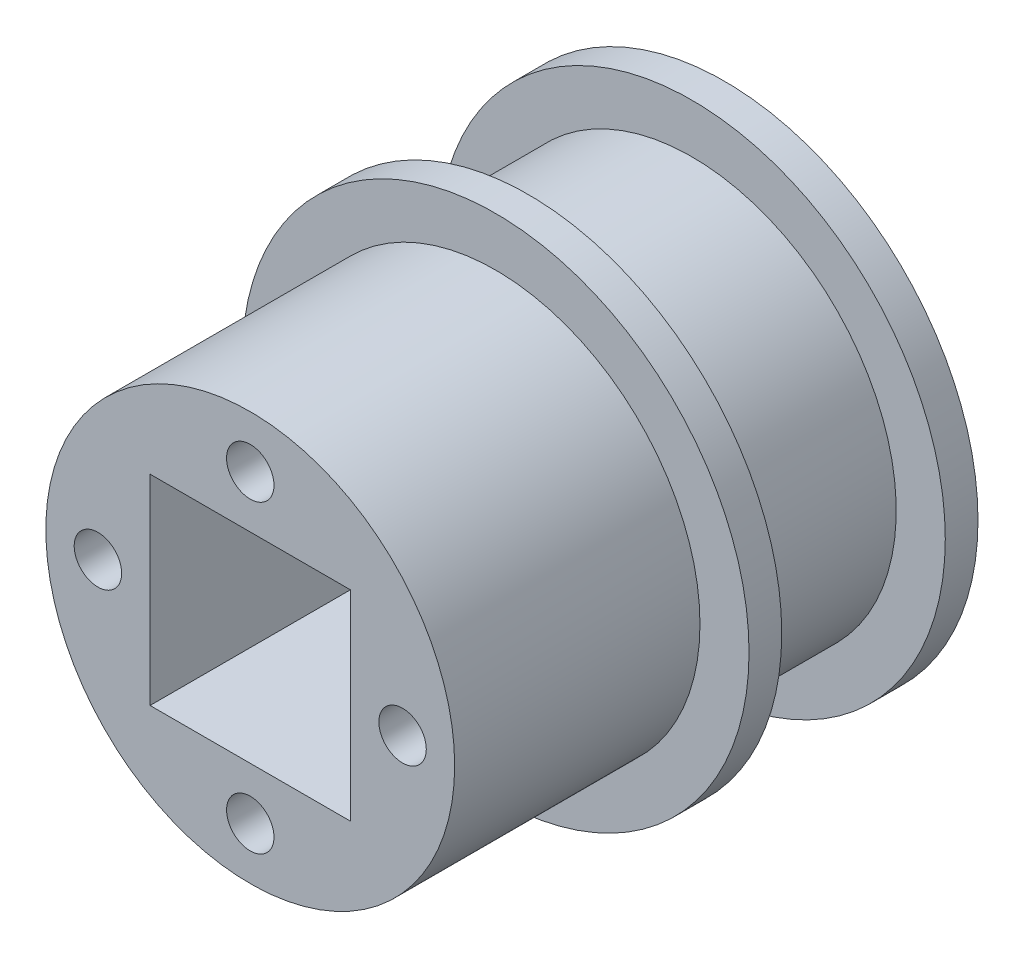
SolidWorks part; units mm, degrees
ref_plane "Front Plane" through (0, 0, 0) normal (0, 0, 1) x (1, 0, 0)
ref_plane "Top Plane" through (0, 0, 0) normal (0, 1, 0) x (1, 0, 0)
ref_plane "Right Plane" through (0, 0, 0) normal (1, 0, 0) x (0, 0, -1)
sketch "Sketch1" plane through (0, 0, 0) normal (0, 0, 1) x (1, 0, 0)
  circle A0 centre (0, 0) radius 12.5
  dimension "D2" = 25
extrude "Boss-Extrude1" add sketch "Sketch1" along normal mid plane 15
sketch "Sketch10" plane through (0, 0, 7.5) normal (0, 0, 1) x (1, 0, 0)
  circle A0 centre (0, 0) radius 12.5
  dimension "D1" = 25
sketch "Sketch13" plane through (0, 0, -7.5) normal (0, 0, -1) x (-1, 0, 0)
  circle A0 centre (0, 0) radius 15.5
  circle A1 centre (0, 0) radius 12.5 construction
  point P2 (0, 0)
  point P3 (0, 0)
  dimension "D1" = 3
extrude "Boss-Extrude2" add sketch "Sketch13" along normal blind 2
sketch "Sketch14" plane through (0, 0, -9.5) normal (0, 0, -1) x (-1, 0, 0)
  circle A0 centre (0, 0) radius 12.5
  circle A1 centre (0, 0) radius 12.5 construction
extrude "Boss-Extrude3" add sketch "Sketch14" along normal blind 10
sketch "Sketch15" plane through (0, 0, -19.5) normal (0, 0, -1) x (-1, 0, 0)
  circle A0 centre (0, 0) radius 15.5
  circle A1 centre (0, 0) radius 15.5 construction
extrude "Boss-Extrude4" add sketch "Sketch15" along normal blind 2
sketch "Sketch8" plane through (0, 0, 7.5) normal (0, 0, 1) x (1, 0, 0)
  line L2 (-6.125, 6.125) -> (6.125, 6.125)
  line L3 (-6.125, 6.125) -> (-6.125, -6.125)
  line L4 (-6.125, -6.125) -> (6.125, -6.125)
  line L5 (6.125, 6.125) -> (6.125, -6.125)
  line L6 (-6.125, 6.125) -> (6.125, -6.125) construction
  line L7 (-6.125, -6.125) -> (6.125, 6.125) construction
  point P5 (0, 0)
  point P14 (0, 0)
  dimension "D1" = 12.25
extrude "Cut-Extrude1" cut sketch "Sketch8" against normal up to next
sketch "Sketch11" plane through (0, 0, 7.5) normal (0, 0, 1) x (1, 0, 0)
  line L0 (6.125, -6.125) -> (6.125, 6.125) construction
  circle A0 centre (9.315, 0) radius 1.45
  circle A1 centre (0, -9.315) radius 1.45
  circle A2 centre (-9.315, 0) radius 1.45
  circle A3 centre (0, 9.315) radius 1.45
  point P13 (0, 0)
  dimension "D1" = 2.9
  dimension "D2" = 3.19
  dimension "D3" = 4
extrude "Cut-Extrude4" cut sketch "Sketch11" against normal up to next
equation "\"drumDiameter\"= 25"
equation "\"D2@Sketch1\"= \"drumDiameter\""
equation "\"drumLength\"=15"
equation "\"foamThickness\"= 5"
equation "\"drumAbove\"= 0.6"
equation "\"holderThicc\"= 2"
equation "\"D1@Boss-Extrude1\"=\"drumLength\""
equation "\"squareBarLength\"= 12.25"
equation "\"D1@Sketch8\"=\"squareBarLength\""
equation "\"D1@Sketch10\"=\"drumDiameter\""
equation "\"toothlen\"= 2.5"
